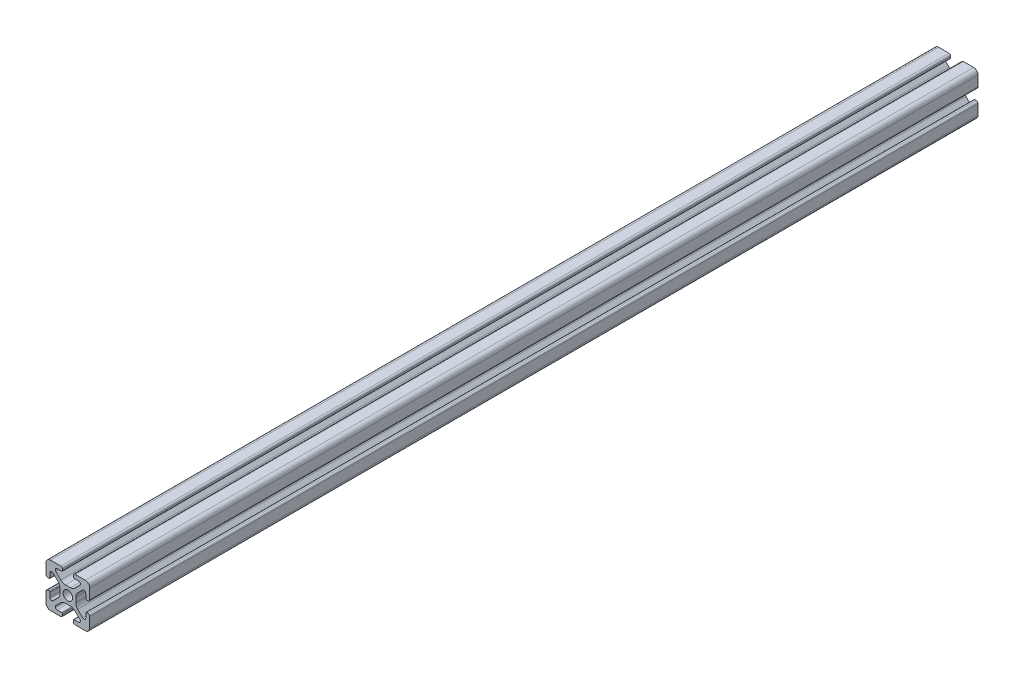
SolidWorks part; units mm, degrees
ref_plane "Front Plane" through (0, 0, 0) normal (0, 0, 1) x (1, 0, 0)
ref_plane "Top Plane" through (0, 0, 0) normal (0, 1, 0) x (1, 0, 0)
ref_plane "Right Plane" through (0, 0, 0) normal (1, 0, 0) x (0, 0, -1)
sketch "Sketch1" plane through (0, 0, 0) normal (0, 0, 1) x (1, 0, 0)
  line L2 (-9.9949, 7.9883) -> (-9.9949, 3.2893)
  line L3 (-7.9883, 9.9949) -> (-3.2893, 9.9949)
  line L4 (-2.5019, 9.2075) -> (-2.5019, 8.4963)
  line L5 (-2.8067, 8.1915) -> (-4.9149, 8.1915)
  line L6 (-5.5076, 6.7606) -> (-3.2528, 4.5058)
  line L7 (-6.7606, 5.5076) -> (-4.5058, 3.2528)
  line L8 (-8.1915, 4.9149) -> (-8.1915, 2.8067)
  line L9 (-8.4963, 2.5019) -> (-9.2075, 2.5019)
  line L11 (-1.1334, 3.6279) -> (1.1334, 3.6279)
  line L12 (-3.6279, 1.1334) -> (-3.6279, -1.1334)
  line L13 (8.4963, 2.5019) -> (9.2075, 2.5019)
  line L14 (8.1915, 4.9149) -> (8.1915, 2.8067)
  line L15 (9.9949, 7.9883) -> (9.9949, 3.2893)
  line L16 (7.9883, 9.9949) -> (3.2893, 9.9949)
  line L17 (2.5019, 9.2075) -> (2.5019, 8.4963)
  line L18 (2.8067, 8.1915) -> (4.9149, 8.1915)
  line L19 (3.6279, 1.1334) -> (3.6279, -1.1334)
  line L20 (5.5076, 6.7606) -> (3.2528, 4.5058)
  line L21 (6.7606, 5.5076) -> (4.5058, 3.2528)
  line L22 (-8.4963, -2.5019) -> (-9.2075, -2.5019)
  line L23 (-8.1915, -4.9149) -> (-8.1915, -2.8067)
  line L24 (-6.7606, -5.5076) -> (-4.5058, -3.2528)
  line L25 (-5.5076, -6.7606) -> (-3.2528, -4.5058)
  line L26 (-2.8067, -8.1915) -> (-4.9149, -8.1915)
  line L27 (-2.5019, -9.2075) -> (-2.5019, -8.4963)
  line L28 (-7.9883, -9.9949) -> (-3.2893, -9.9949)
  line L29 (-9.9949, -7.9883) -> (-9.9949, -3.2893)
  line L30 (9.9949, -7.9883) -> (9.9949, -3.2893)
  line L31 (7.9883, -9.9949) -> (3.2893, -9.9949)
  line L32 (2.5019, -9.2075) -> (2.5019, -8.4963)
  line L33 (2.8067, -8.1915) -> (4.9149, -8.1915)
  line L34 (5.5076, -6.7606) -> (3.2528, -4.5058)
  line L35 (6.7606, -5.5076) -> (4.5058, -3.2528)
  line L36 (8.1915, -4.9149) -> (8.1915, -2.8067)
  line L37 (8.4963, -2.5019) -> (9.2075, -2.5019)
  line L38 (-1.1334, -3.6279) -> (1.1334, -3.6279)
  circle A0 centre (0, 0) radius 2.1463
  arc A1 (-9.9949, 7.9883) -> (-7.9883, 9.9949) centre (-7.9883, 7.9883) cw
  arc A2 (-6.7606, 5.5076) -> (-8.1915, 4.9149) centre (-7.3533, 4.9149) ccw
  arc A3 (-4.9149, 8.1915) -> (-5.5076, 6.7606) centre (-4.9149, 7.3533) ccw
  arc A4 (-3.2893, 9.9949) -> (-2.5019, 9.2075) centre (-3.2893, 9.2075) cw
  arc A5 (-9.9949, 3.2893) -> (-9.2075, 2.5019) centre (-9.2075, 3.2893) ccw
  arc A6 (-8.1915, 2.8067) -> (-8.4963, 2.5019) centre (-8.4963, 2.8067) cw
  arc A7 (-2.5019, 8.4963) -> (-2.8067, 8.1915) centre (-2.8067, 8.4963) cw
  arc A8 (-1.1334, 3.6279) -> (-3.2528, 4.5058) centre (-1.1334, 6.6251) cw
  arc A9 (-3.6279, 1.1334) -> (-4.5058, 3.2528) centre (-6.6251, 1.1334) ccw
  arc A10 (8.1915, 2.8067) -> (8.4963, 2.5019) centre (8.4963, 2.8067) ccw
  arc A11 (9.9949, 3.2893) -> (9.2075, 2.5019) centre (9.2075, 3.2893) cw
  arc A12 (9.9949, 7.9883) -> (7.9883, 9.9949) centre (7.9883, 7.9883) ccw
  arc A13 (3.2893, 9.9949) -> (2.5019, 9.2075) centre (3.2893, 9.2075) ccw
  arc A14 (2.5019, 8.4963) -> (2.8067, 8.1915) centre (2.8067, 8.4963) ccw
  arc A15 (1.1334, 3.6279) -> (3.2528, 4.5058) centre (1.1334, 6.6251) ccw
  arc A16 (3.6279, 1.1334) -> (4.5058, 3.2528) centre (6.6251, 1.1334) cw
  arc A17 (6.7606, 5.5076) -> (8.1915, 4.9149) centre (7.3533, 4.9149) cw
  arc A18 (4.9149, 8.1915) -> (5.5076, 6.7606) centre (4.9149, 7.3533) cw
  arc A19 (-3.6279, -1.1334) -> (-4.5058, -3.2528) centre (-6.6251, -1.1334) cw
  arc A20 (-1.1334, -3.6279) -> (-3.2528, -4.5058) centre (-1.1334, -6.6251) ccw
  arc A21 (-2.5019, -8.4963) -> (-2.8067, -8.1915) centre (-2.8067, -8.4963) ccw
  arc A22 (-8.1915, -2.8067) -> (-8.4963, -2.5019) centre (-8.4963, -2.8067) ccw
  arc A23 (-9.9949, -3.2893) -> (-9.2075, -2.5019) centre (-9.2075, -3.2893) cw
  arc A24 (-3.2893, -9.9949) -> (-2.5019, -9.2075) centre (-3.2893, -9.2075) ccw
  arc A25 (-4.9149, -8.1915) -> (-5.5076, -6.7606) centre (-4.9149, -7.3533) cw
  arc A26 (-6.7606, -5.5076) -> (-8.1915, -4.9149) centre (-7.3533, -4.9149) cw
  arc A27 (-9.9949, -7.9883) -> (-7.9883, -9.9949) centre (-7.9883, -7.9883) ccw
  arc A28 (9.9949, -7.9883) -> (7.9883, -9.9949) centre (7.9883, -7.9883) cw
  arc A29 (6.7606, -5.5076) -> (8.1915, -4.9149) centre (7.3533, -4.9149) ccw
  arc A30 (4.9149, -8.1915) -> (5.5076, -6.7606) centre (4.9149, -7.3533) ccw
  arc A31 (3.2893, -9.9949) -> (2.5019, -9.2075) centre (3.2893, -9.2075) cw
  arc A32 (9.9949, -3.2893) -> (9.2075, -2.5019) centre (9.2075, -3.2893) ccw
  arc A33 (8.1915, -2.8067) -> (8.4963, -2.5019) centre (8.4963, -2.8067) cw
  arc A34 (2.5019, -8.4963) -> (2.8067, -8.1915) centre (2.8067, -8.4963) cw
  arc A35 (1.1334, -3.6279) -> (3.2528, -4.5058) centre (1.1334, -6.6251) cw
  arc A36 (3.6279, -1.1334) -> (4.5058, -3.2528) centre (6.6251, -1.1334) ccw
extrude "Boss-Extrude1" add sketch "Sketch1" along normal mid plane 406.4
